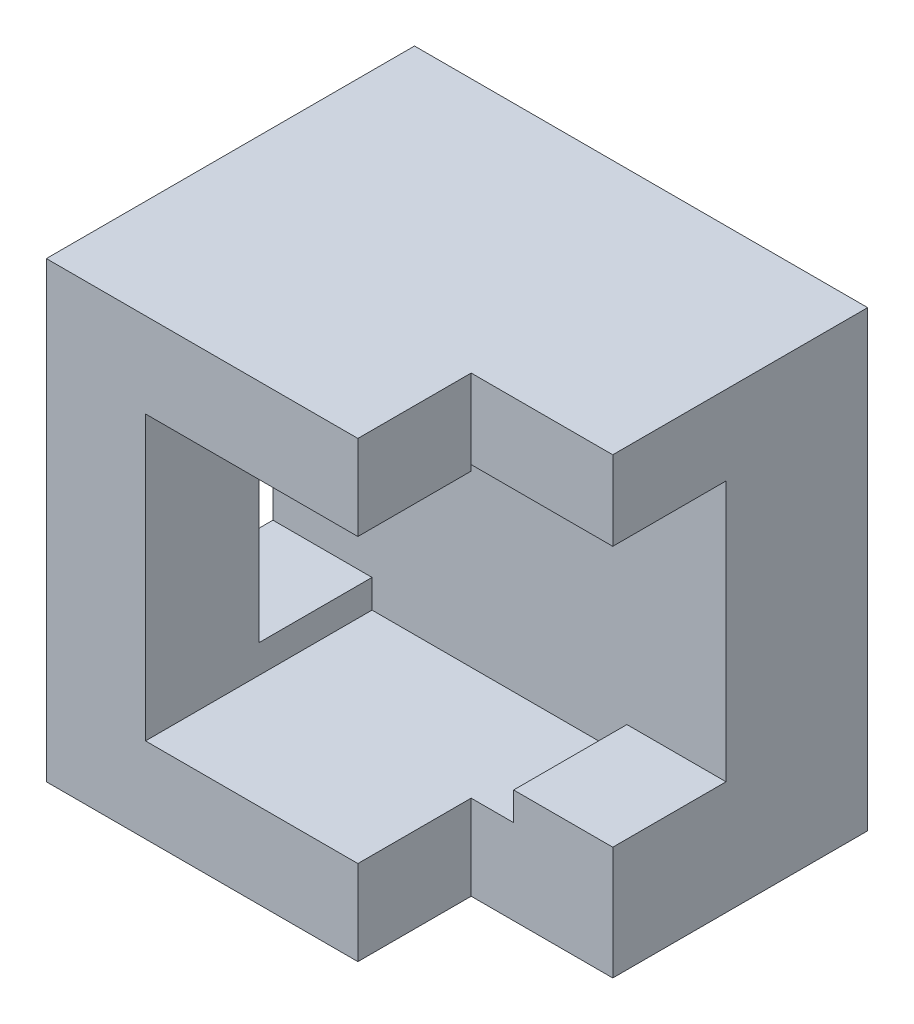
SolidWorks part; units mm, degrees
ref_plane "Ön Düzlem" through (0, 0, 0) normal (0, 0, 1) x (1, 0, 0)
ref_plane "Üst Düzlem" through (0, 0, 0) normal (0, 1, 0) x (1, 0, 0)
ref_plane "Sağ Düzlem" through (0, 0, 0) normal (1, 0, 0) x (0, 0, -1)
sketch "Çizim1" plane through (0, 0, 0) normal (0, 0, 1) x (1, 0, 0)
  line L1 (-40, 40) -> (40, 40)
  line L2 (-40, 40) -> (-40, -40)
  line L3 (-40, -40) -> (40, -40)
  line L4 (40, 40) -> (40, -40)
  point P4 (0, 40)
  point P6 (-40, 0)
  dimension "D1" = 80
  dimension "D2" = 80
extrude "Yükseklik-Ekstrüzyon1" add sketch "Çizim1" along normal blind 65
sketch "Çizim3" plane through (0, 0, 65) normal (0, 0, 1) x (1, 0, 0)
  line L0 (40, 40) -> (-40, 40) construction
  line L1 (-22.5, 25) -> (22.5, 25)
  line L2 (-22.5, 25) -> (-22.5, -25)
  line L3 (-22.5, -25) -> (22.5, -25)
  line L4 (22.5, 25) -> (22.5, -25)
  line L6 (-40, 40) -> (-40, -40) construction
  dimension "D1" = 45
  dimension "D2" = 50
  dimension "D3" = 15
  dimension "D4" = 17.5
extrude "Kes-Ekstrüzyon1" cut sketch "Çizim3" against normal blind 40
sketch "Çizim4" plane through (40, 0, 0) normal (1, 0, 0) x (0, 0, -1)
  line L0 (-45, 393.5) -> (-45, -56.5) construction
  line L1 (-45, -20) -> (-25, -20)
  line L2 (-45, -20) -> (-45, 26)
  line L3 (-45, 26) -> (-25, 26)
  line L4 (-25, -20) -> (-25, 26)
  line L5 (-25, 35.2) -> (-25, -28) construction
  line L6 (-65, -40) -> (0, -40) construction
  line L7 (-65, 40) -> (0, 40) construction
  point P8 (-35, -20)
  dimension "D1" = 20
  dimension "D2" = 14
extrude "Kes-Ekstrüzyon2" cut sketch "Çizim4" against normal blind 80
sketch "Çizim5" plane through (0, -40, 0) normal (0, -1, 0) x (1, 0, 0)
  line L0 (15, 45) -> (15, 65)
  line L1 (15, 45) -> (40, 45)
  line L2 (40, 45) -> (40, 65)
  line L3 (40, 65) -> (15, 65)
extrude "Kes-Ekstrüzyon3" cut sketch "Çizim5" against normal through all
